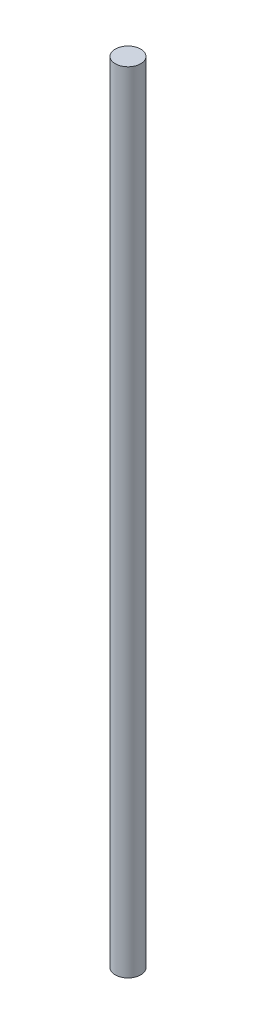
SolidWorks part; units mm, degrees
ref_plane "Front Plane" through (0, 0, 0) normal (0, 0, 1) x (1, 0, 0)
ref_plane "Top Plane" through (0, 0, 0) normal (0, 1, 0) x (1, 0, 0)
ref_plane "Right Plane" through (0, 0, 0) normal (1, 0, 0) x (0, 0, -1)
sketch "Sketch1" plane through (0, 0, 0) normal (0, 1, 0) x (1, 0, 0)
  circle A0 centre (0, 0) radius 2
  dimension "D1" = 4
extrude "Boss-Extrude1" add sketch "Sketch1" along normal blind 124
